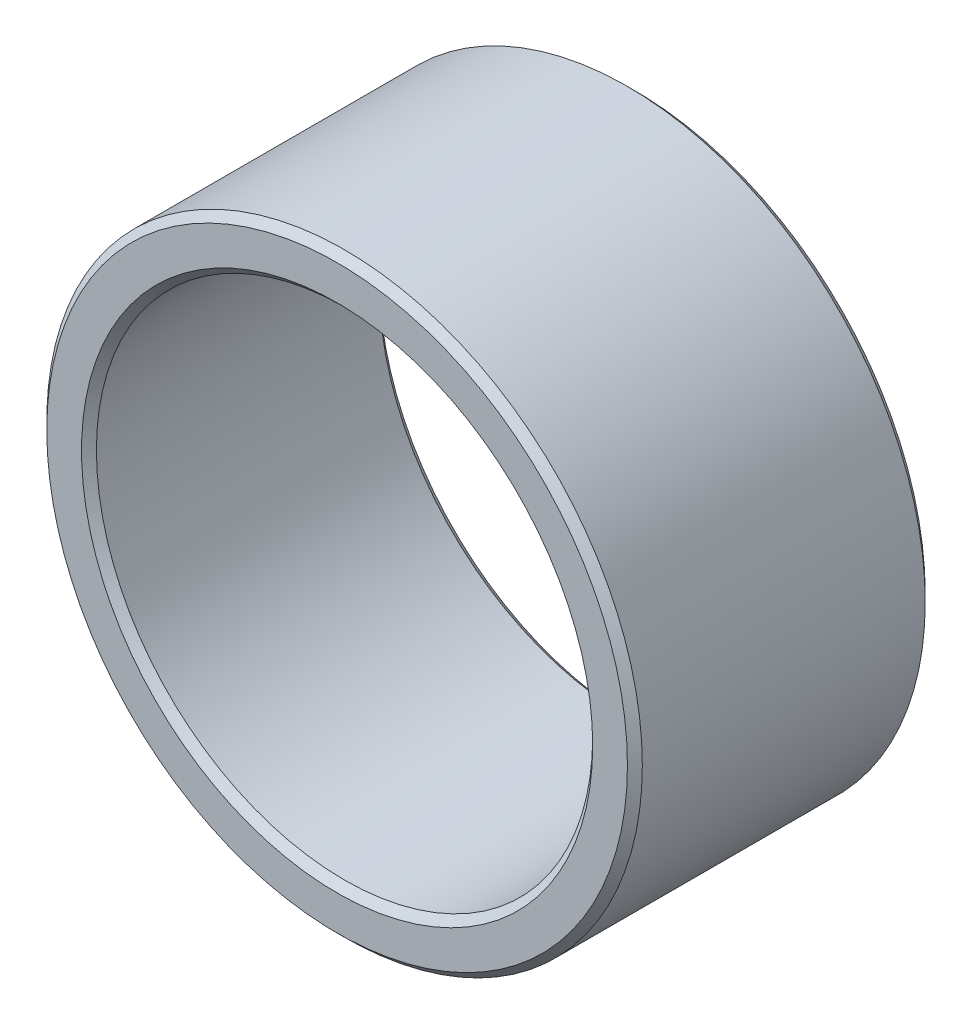
SolidWorks part; units mm, degrees
ref_plane "前视基准面" through (0, 0, 0) normal (0, 0, 1) x (1, 0, 0)
ref_plane "上视基准面" through (0, 0, 0) normal (0, 1, 0) x (1, 0, 0)
ref_plane "右视基准面" through (0, 0, 0) normal (1, 0, 0) x (0, 0, -1)
sketch "草图1" plane through (0, 0, 0) normal (0, 0, 1) x (1, 0, 0)
  circle A0 centre (0, 0) radius 10
  circle A1 centre (0, 0) radius 12
  dimension "D1" = 20
  dimension "D2" = 24
extrude "凸台-拉伸1" add sketch "草图1" along normal blind 12
chamfer "倒角1" distance 0.3 angle 45 4 edges at (10, 0, 0) (12, 0, 0) (10, 0, 12) (12, 0, 12)
